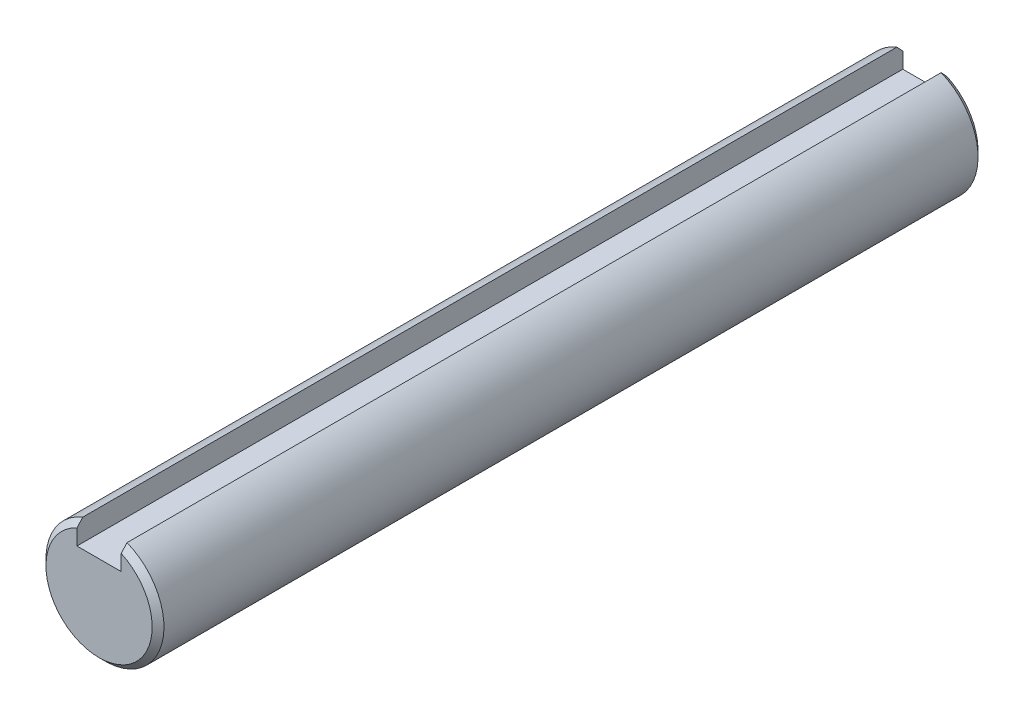
SolidWorks part; units mm, degrees
ref_plane "Front Plane" through (0, 0, 0) normal (0, 0, 1) x (1, 0, 0)
ref_plane "Top Plane" through (0, 0, 0) normal (0, 1, 0) x (1, 0, 0)
ref_plane "Right Plane" through (0, 0, 0) normal (1, 0, 0) x (0, 0, -1)
sketch "Sketch1" plane through (0, 0, 0) normal (0, 0, 1) x (1, 0, 0)
  line L0 (-2.2451, -2.2451) -> (-1.1225, -1.1225) construction
  line L1 (3.4925, 0) -> (-3.4925, 0) construction
  line L2 (0, 0) -> (0, 3.175) construction
  line L4 (-1.1906, 3.175) -> (1.1906, 3.175) construction
  line L5 (-1.1906, 3.175) -> (-1.1906, 1.7527) construction
  line L6 (-1.1906, 1.7527) -> (1.1906, 1.7527) construction
  line L7 (1.1906, 3.175) -> (1.1906, 1.7527) construction
  line L8 (-1.1906, 3.175) -> (1.1906, 1.7527) construction
  line L9 (-1.1906, 1.7527) -> (1.1906, 3.175) construction
  circle A0 centre (0, 0) radius 1.5875 construction
  circle A1 centre (0, 0) radius 3.175 construction
  point P6 (0, 2.4638)
  point P16 (-1.1906, 2.9433)
  dimension "Diameter" = 6.35
  dimension "Thread Dia" = 3.175
  dimension "D1" = 45
  dimension "Keyway Wd" = 2.3813
  dimension "Keyway Ht" = 1.1906
sketch "Sketch2" plane through (0, 0, 0) normal (1, 0, 0) x (0, 0, -1)
  line L0 (-38.1, -3.175) -> (38.1, -3.175) construction
  line L1 (0, 3.175) -> (0, -3.175) construction
  line L2 (0, 3.175) -> (0, -3.175) construction
  point P3 (25.4, -3.175)
  point P4 (-25.4, -3.175)
  dimension "Length" = 76.2
  dimension "D1" = 12.7
  dimension "D2" = 12.7
sketch "Sketch3" plane through (0, 0, 0) normal (0, 0, 1) x (1, 0, 0)
  circle A1 centre (0, 0) radius 3.175 construction
  circle A3 centre (0, 0) radius 3.175
extrude "Boss-Extrude2" add sketch "Sketch3" along normal blind 25.4 and the other way blind 19.05
sketch "Sketch10" plane through (0, 0, 0) normal (0, 0, 1) x (1, 0, 0)
  line L1 (1.1906, 3.175) -> (1.1906, 1.7527) construction
  line L2 (-1.1906, 1.7527) -> (1.1906, 1.7527) construction
  line L3 (-1.1906, 3.175) -> (-1.1906, 1.7527) construction
  line L4 (-1.1906, 3.175) -> (1.1906, 3.175) construction
  line L5 (1.1906, 3.175) -> (1.1906, 1.7527)
  line L6 (-1.1906, 1.7527) -> (1.1906, 1.7527)
  line L7 (-1.1906, 3.175) -> (-1.1906, 1.7527)
  line L8 (-1.1906, 3.175) -> (1.1906, 3.175)
extrude "Cut-Extrude5" cut sketch "Sketch10" against normal through all both and the other way through all
chamfer "Chamfer1" distance 0.3175 angle 45 2 edges at (0, -3.175, 25.4) (0, -3.175, -19.05)
equation "\"D1@Chamfer1\"= \"Diameter@Sketch1\" / 20"
equation "\"D1@Sketch2\"=\"Diameter@Sketch1\"*2"
equation "\"D2@Sketch2\"=\"D1@Sketch2\""
